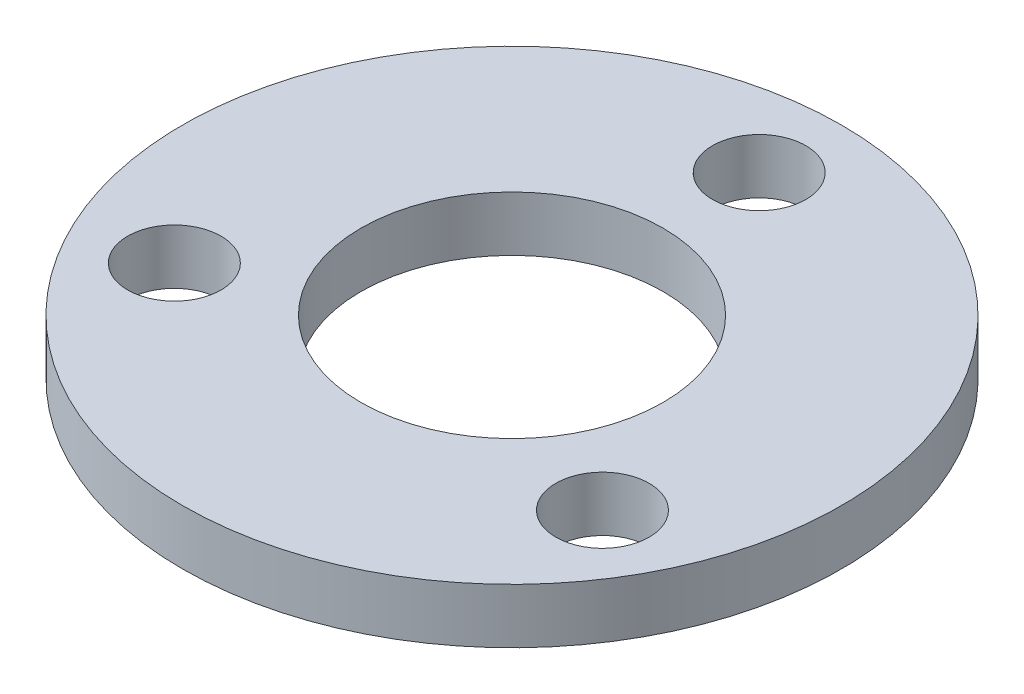
SolidWorks part; units mm, degrees
ref_plane "Спереди" through (0, 0, 0) normal (0, 0, 1) x (1, 0, 0)
ref_plane "Сверху" through (0, 0, 0) normal (0, 1, 0) x (1, 0, 0)
ref_plane "Справа" through (0, 0, 0) normal (1, 0, 0) x (0, 0, -1)
sketch "Эскиз1" plane through (0, 0, 0) normal (0, 1, 0) x (1, 0, 0)
  line L0 (0, 0) -> (0, 21.901) construction
  line L1 (0, 0) -> (-18.0489, -10.4205) construction
  line L2 (0, 0) -> (18.1135, -10.4578) construction
  circle A0 centre (0, 0) radius 12
  circle A1 centre (0, 0) radius 9 construction
  circle A2 centre (0, 9) radius 1.7
  circle A3 centre (0, 0) radius 10.7 construction
  circle A4 centre (7.7942, -4.5) radius 1.7
  circle A5 centre (-7.7942, -4.5) radius 1.7
  circle A7 centre (0, 0) radius 5.5
  dimension "D1" = 24
  dimension "D2" = 21.4
  dimension "D3" = 18
  dimension "D4" = 11
  dimension "D6" = 120
  dimension "D5" = 120
extrude "Бобышка-Вытянуть1" add sketch "Эскиз1" along normal blind 2
